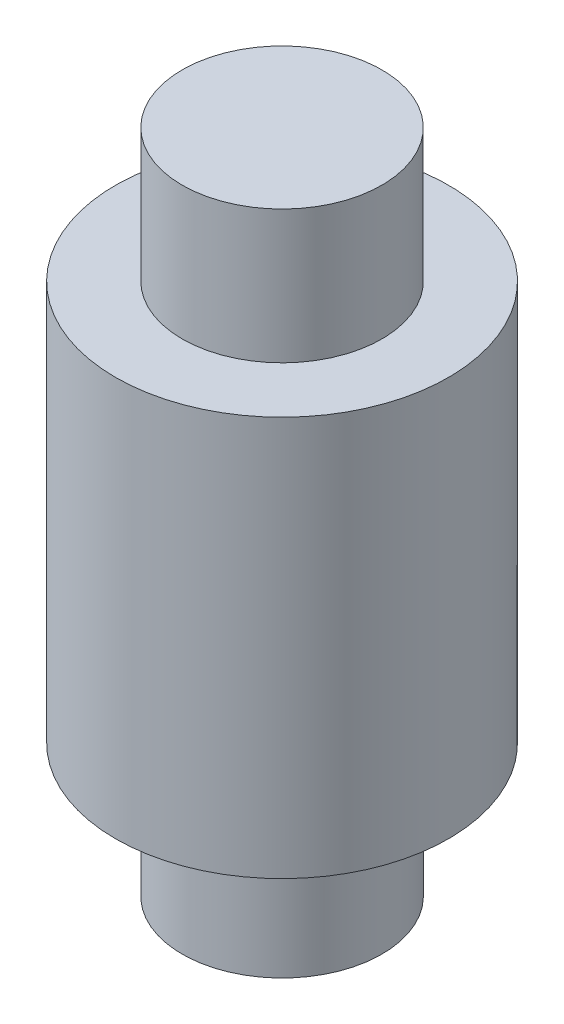
SolidWorks part; units mm, degrees
ref_plane "Спереди" through (0, 0, 0) normal (0, 0, 1) x (1, 0, 0)
ref_plane "Сверху" through (0, 0, 0) normal (0, 1, 0) x (1, 0, 0)
ref_plane "Справа" through (0, 0, 0) normal (1, 0, 0) x (0, 0, -1)
sketch "Эскиз1" plane through (0, 0, 0) normal (0, 1, 0) x (1, 0, 0)
  circle A0 centre (0, 0) radius 2.5
  dimension "D1" = 5
extrude "Бобышка-Вытянуть1" add sketch "Эскиз1" along normal blind 6
sketch "Эскиз2" plane through (0, 6, 0) normal (0, 1, 0) x (1, 0, 0)
  circle A0 centre (0, 0) radius 1.5
  dimension "D1" = 3
extrude "Бобышка-Вытянуть2" add sketch "Эскиз2" along normal blind 2
sketch "Эскиз4" plane through (0, 0, 0) normal (0, -1, 0) x (1, 0, 0)
  circle A0 centre (0, 0) radius 1.5
  circle A1 centre (0, 0) radius 1.5 construction
extrude "Бобышка-Вытянуть3" add sketch "Эскиз4" along normal blind 2
